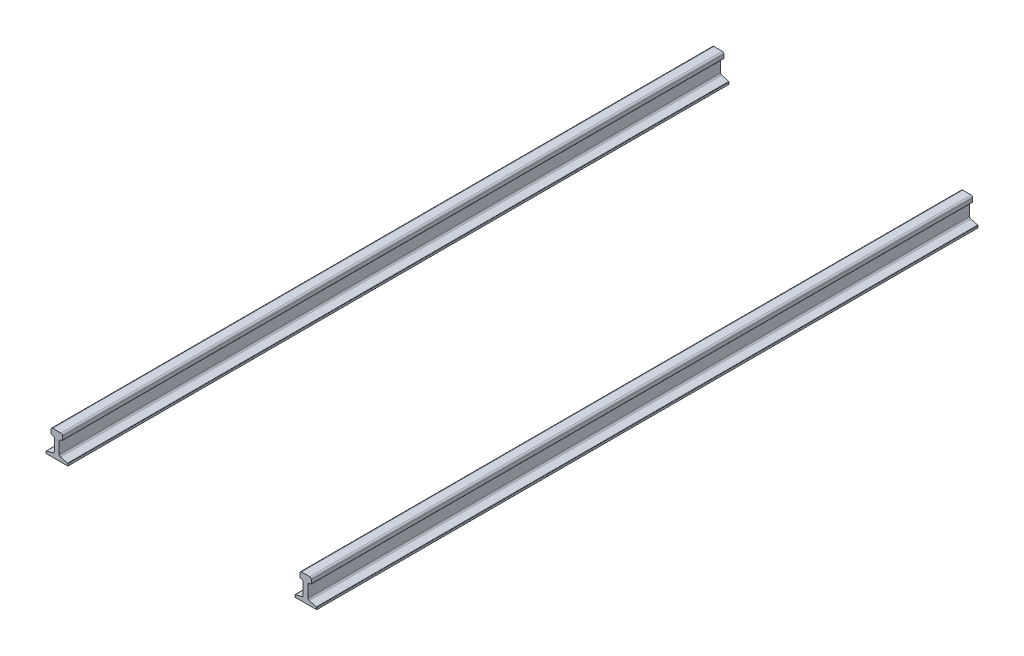
SolidWorks part; units mm, degrees
ref_plane "前视基准面" through (0, 0, 0) normal (0, 0, 1) x (1, 0, 0)
ref_plane "上视基准面" through (0, 0, 0) normal (0, 1, 0) x (1, 0, 0)
ref_plane "右视基准面" through (0, 0, 0) normal (1, 0, 0) x (0, 0, -1)
sketch "草图1" plane through (0, 0, 0) normal (0, 0, 1) x (1, 0, 0)
  line L0 (0, -1000) -> (0, 49000) construction
  line L1 (-35, -1000.4455) -> (-35, 48999.5545) construction
  line L2 (35, -1000.1485) -> (35, 48999.8515) construction
  line L3 (-65, -895.965) -> (-65, 49104.035) construction
  line L4 (67, -918.509) -> (67, 49081.491) construction
  line L5 (-15, -968.6067) -> (-15, 49031.3933) construction
  line L6 (15, -969.4417) -> (15, 49030.5583) construction
  line L7 (-1051.2415, 49.6) -> (48948.7585, 49.6) construction
  line L8 (-1057, -54.6) -> (48943, -54.6) construction
  line L9 (-35, 49.6) -> (-35, 83.5)
  line L10 (-1000, 0) -> (49000, 0) construction
  line L11 (-35, 83.5) -> (35, 83.5)
  line L12 (35, 83.5) -> (35, 49.6)
  line L13 (-35, 49.6) -> (365, -50.4) construction
  line L14 (35, 49.6) -> (-365, -50.4) construction
  line L15 (-35, 49.6) -> (-15, 44.6)
  line L16 (35, 49.6) -> (15, 44.6)
  line L17 (-65, -68.5) -> (67, -68.5)
  line L18 (-15, 44.6) -> (-15, -42.1)
  line L19 (15, 44.6) -> (15, -41.6)
  line L20 (-65, -54.6) -> (-15, -42.1)
  line L21 (67, -54.6) -> (67, -68.5)
  line L22 (15, -41.6) -> (67, -54.6)
  line L23 (-65, -54.6) -> (-65, -68.5)
  dimension "D1" = 35
  dimension "D2" = 35
  dimension "D3" = 65
  dimension "D4" = 67
  dimension "D5" = 15
  dimension "D6" = 15
  dimension "D7" = 49.6
  dimension "D9" = 83.5
  dimension "D10" = 100
  dimension "D11" = 400
  dimension "D12" = 100
  dimension "D13" = 400
  dimension "D14" = 152
  dimension "D16" = 54.6
extrude "拉伸1" add sketch "草图1" against normal blind 4000
fillet "圆角1" radius 10 2 edges at (-15, -42.1, -2000) (15, -41.6, -2000)
fillet "圆角2" radius 8 2 edges at (-15, 44.6, -2000) (15, 44.6, -2000)
fillet "圆角3" radius 3 2 edges at (35, 49.6, -2000) (-35, 49.6, -2000)
fillet "圆角4" radius 10 2 edges at (-35, 83.5, -2000) (35, 83.5, -2000)
fillet "圆角5" radius 3 2 edges at (-65, -54.6, -2000) (67, -54.6, -2000)
pattern_linear "阵列(线性)1" count 2 spacing 1505 along (-1, 0, 0) of bodies 101
